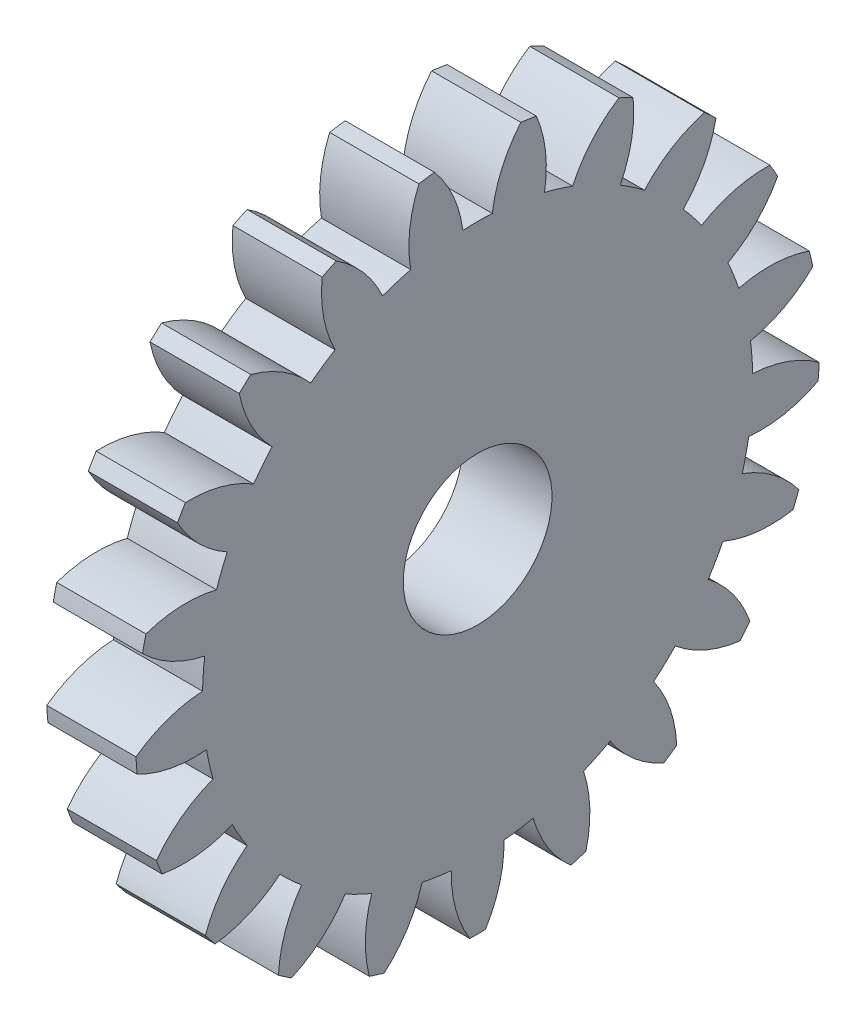
SolidWorks part; units mm, degrees
ref_plane "Plane1" through (0, 0, 0) normal (0, 0, 1) x (1, 0, 0)
ref_plane "Plane2" through (0, 0, 0) normal (0, 1, 0) x (1, 0, 0)
ref_plane "Plane3" through (0, 0, 0) normal (1, 0, 0) x (0, 0, -1)
sketch "HoldingSke" plane through (0, 0, 0) normal (0, 1, 0) x (1, 0, 0)
  line L0 (0, 0) -> (0.9336, -0.3584)
  line L1 (-15, 0) -> (100, 0) construction
  line L2 (0, 0) -> (-2.1039, 2.3779)
  line L3 (0, 0) -> (-11.863, 4.5341)
  line L4 (0, 0) -> (8.0624, 3.0949)
  line L5 (0, 0) -> (-46.8476, -17.4728)
  line L6 (0, 0) -> (-9.9476, -6.7116)
  line L7 (-2.1039, 2.3779) -> (8.6586, 51.2059)
  line L8 (-76.2, 54.61) -> (-75.3, 54.61)
  line L9 (-71.009, 38.7566) -> (-53.1078, 45.2721)
  line L10 (-76.2, 71.12) -> (104.1128, 71.12)
  line L11 (0, 0) -> (-12, 0)
  line L12 (-76.2, 101.6) -> (-76.162, 101.6)
  line L13 (24.9733, 27.94) -> (52.9518, 28.4284)
  line L14 (24.9733, 27.94) -> (24.9743, 27.94)
  line L15 (24.9733, 27.94) -> (100.4006, 29.5858)
  line L16 (-63.627, -1) -> (-12.827, -1)
  circle A0 centre (0, 0) radius 2.5
  circle A1 centre (0, 0) radius 9.249
  circle A2 centre (0, 0) radius 37.5
  circle A3 centre (0, 0) radius 2.5
  dimension "MHD" = 18.498
  dimension "Hub_dia" = 75
  dimension "Bore" = 5
  dimension "MBD" = 5
  dimension "Num_teeth" = 21
  dimension "Pitch" = 1
  dimension "Overall_len" = 50
  dimension "Show_teeth" = 21
  dimension "Thickness" = 12
  dimension "OAL" = 50.0001
  dimension "T_dim" = 0.9
  dimension "Ap" = 20
  dimension "H" = 19.05
  dimension "Pitch_radius" = 180.3128
  dimension "Width" = 12
  dimension "Backlash" = 0.038
  dimension "Addendum_fac" = 1
  dimension "Dedendum_fac" = 1.25
  dimension "Clearance_fac" = 0.25
  dimension "Dedendum_add" = 0.001
  dimension "Module" = 1
sketch "BasProSke" plane through (0, 0, 0) normal (0, 1, 0) x (1, 0, 0)
  line L0 (-10, 0) -> (60, 0) construction
  line L1 (0, 0) -> (0, 11.5)
  line L2 (0, 0) -> (12, 0)
  line L3 (12, 0) -> (12, 11.5)
  line L4 (12, 11.5) -> (0, 11.5)
  dimension "Thickness" = 12
  dimension "Diameter" = 23
revolve "Base-Revolve" add sketch "BasProSke" angle 360 about L0
sketch "TooCutSke" plane through (0, 0, 0) normal (1, 0, 0) x (0, 0, -1)
  line L1 (0, 0) -> (0, 107) construction
  line L2 (0, 0) -> (-0.8511, 10.4654) construction
  line L3 (0, 0) -> (-3.1226, 20.7168) construction
  line L4 (-0.8511, 10.4654) -> (-1.5613, 10.3584) construction
  arc A0 (0.4953, 9.2357) -> (-0.4953, 9.2357) centre (0, 0) ccw
  arc A1 (1.4725, 11.431) -> (-1.4725, 11.431) centre (0, 0) ccw
  circle A2 centre (0, 0) radius 10.5 construction
  circle A3 centre (0, 0) radius 9.8668 construction
  arc A4 (-0.4953, 9.2357) -> (-1.4725, 11.431) centre (-4.6605, 8.6967) ccw
  arc A5 (1.4725, 11.431) -> (0.4953, 9.2357) centre (4.6605, 8.6967) ccw
  dimension "Root_dia" = 18.498
  dimension "Overcut_dia" = 23.0508
  dimension "Pitch_dia" = 21
  dimension "Base_dia" = 19.7335
  dimension "Flank_rad" = 4.2
  dimension "Half_ang" = 8.571
  dimension "Half_CT" = 0.7182
extrude "ToothCut" cut sketch "TooCutSke" along normal through all
fillet "Breaks" [suppressed] radius 0.02
fillet "RootFillets" [suppressed] radius 0.251
pattern_circular "TeethCuts" count 21 every 17.143 about axis through (-10, 0, 0) along (1, 0, 0) of "ToothCut", "RootFillets", "Breaks"
sketch "HubNeaOneSke" plane through (0, 0, 0) normal (-1, 0, 0) x (0, 0, 1)
  circle A0 centre (0, 0) radius 9.249
  dimension "Diameter" = 18.498
extrude "HubNearOne" [suppressed] add sketch "HubNeaOneSke" along normal blind 38.0001
sketch "HubNeaBotSke" plane through (0, 0, 0) normal (-1, 0, 0) x (0, 0, 1)
  circle A0 centre (0, 0) radius 9.249
  dimension "Diameter" = 18.498
extrude "HubNearBoth" [suppressed] add sketch "HubNeaBotSke" along normal blind 19
ref_plane "FarPln" through (12, 0, 0) normal (1, 0, 0) x (0, 0, -1)
sketch "HubFarSke" plane through (12, 0, 0) normal (1, 0, 0) x (0, 0, -1)
  circle A0 centre (0, 0) radius 9.249
  dimension "Diameter" = 18.498
extrude "HubFar" [suppressed] add sketch "HubFarSke" along normal blind 19
sketch "BorSke" plane through (0, 0, 0) normal (1, 0, 0) x (0, 0, -1)
  circle A0 centre (0, 0) radius 2.5
  dimension "Diameter" = 5
extrude "Bore" cut sketch "BorSke" along normal mid plane 100.0001
sketch "KeySke" plane through (0, 0, 0) normal (1, 0, 0) x (0, 0, -1)
  line L0 (-1, 0) -> (-1, 3.4)
  line L1 (-1, 3.4) -> (1, 3.4)
  line L2 (1, 3.4) -> (1, 0)
  line L3 (0, 0) -> (0, 34) construction
  line L4 (-1, 0) -> (1, 0)
  dimension "Offset" = 3.4
  dimension "Width" = 2
extrude "Keyway" [suppressed] cut sketch "KeySke" along normal mid plane 100.0001
pattern_circular "Keyway2" [suppressed] count 2 every 90 about axis through (-10, 0, 0) along (1, 0, 0)
sketch "Croquis1" plane through (0, 0, 0) normal (-1, 0, 0) x (0, 0, 1)
  line L1 (-12.6891, 12.6586) -> (14.0592, 12.6586)
  line L2 (-12.6891, 12.6586) -> (-12.6891, -12.7196)
  line L3 (-12.6891, -12.7196) -> (14.0592, -12.7196)
  line L4 (14.0592, 12.6586) -> (14.0592, -12.7196)
extrude "Cortar-Extruir1" cut sketch "Croquis1" against normal blind 9
equation "' \"Module@HoldingSke\" = 6.35"
equation "' \"Num_teeth@HoldingSke\" = 12"
equation "' \"Ap@HoldingSke\" =  20"
equation "' \"Ap@HoldingSke\" = 20"
equation "' \"Width@HoldingSke\" = 0.5 * 25.4"
equation "' \"Hub_dia@HoldingSke\"= 1 * 25.4"
equation "' \"Hub_dia@HoldingSke\" = 1 * 25.4"
equation "' \"Overall_len@HoldingSke\" = 1.0 * 25.4"
equation "' \"Bore@HoldingSke\" = 0.75 * 25.4"
equation "' \"T_dim@HoldingSke\" = 0.1 * 25.4"
equation "' \"Width@KeySke\" = 0.25 * 25.4"
equation "' \"Show_teeth@HoldingSke\" = 13"
equation "' \"Backlash@HoldingSke\" = 0.009 * 25.4"
equation "' \"Addendum_fac@HoldingSke\" = 1.0"
equation "' \"Dedendum_fac@HoldingSke\" = 1.25"
equation "' \"Dedendum_add@HoldingSke\" = 0.00005 * 25.4"
equation "' \"Clearance_fac@HoldingSke\" = 0.25"
equation "\"Pitch@HoldingSke\" = 1 / \"Module@HoldingSke\""
equation "\"Overcut_dia@TooCutSke\" = (\"Num_teeth@HoldingSke\" + 2 * \"Addendum_fac@HoldingSke\") / \"Pitch@HoldingSke\" + 0.002 * 25.4"
equation "\"Pitch_dia@TooCutSke\" = \"Num_teeth@HoldingSke\" / \"Pitch@HoldingSke\""
equation "\"Base_dia@TooCutSke\" = \"Num_teeth@HoldingSke\" / \"Pitch@HoldingSke\" * cos((\"Ap@HoldingSke\"  * 3.14159265 / 180))"
equation "\"Root_dia@TooCutSke\" = (\"Num_teeth@HoldingSke\" + 2) / \"Pitch@HoldingSke\" - 2 * (\"Addendum_fac@HoldingSke\" + \"Dedendum_fac@HoldingSke\") / \"Pitch@HoldingSke\" - \"Dedendum_add@HoldingSke\" * 2"
equation "\"Half_ang@TooCutSke\" = 180 / \"Num_teeth@HoldingSke\""
equation "\"Half_CT@TooCutSke\" = \"Num_teeth@HoldingSke\" / \"Pitch@HoldingSke\" * sin((3.14159265 / 2 / \"Num_teeth@HoldingSke\")) / 2 - 7 * \"Backlash@HoldingSke\" / 4"
equation "\"Flank_rad@TooCutSke\" = \"Num_teeth@HoldingSke\" / \"Pitch@HoldingSke\" / 5"
equation "\"Radius@RootFillets\" = \"Clearance_fac@HoldingSke\" / \"Pitch@HoldingSke\" + \"Dedendum_add@HoldingSke\""
equation "\"Break_rad@Breaks\" = 0.02 / \"Pitch@HoldingSke\""
equation "\"Thickness@HoldingSke\" = \"Width@HoldingSke\""
equation "\"OAL@HoldingSke\" = \"Thickness@HoldingSke\""
equation "\"MHD@HoldingSke\" = (\"Num_teeth@HoldingSke\" + 2) / \"Pitch@HoldingSke\" - 2 * (\"Addendum_fac@HoldingSke\" + \"Dedendum_fac@HoldingSke\")  / \"Pitch@HoldingSke\" - \"Dedendum_add@HoldingSke\" * 2"
equation "\"MBD@HoldingSke\" = (\"Num_teeth@HoldingSke\" + 2) / \"Pitch@HoldingSke\" - 2 * (\"Addendum_fac@HoldingSke\" + \"Dedendum_fac@HoldingSke\")  / \"Pitch@HoldingSke\" - \"Dedendum_add@HoldingSke\" * 2 - 0.002 * 25.4"
equation "\"MHD@HoldingSke\" = ((sgn( \"MHD@HoldingSke\" - \"Hub_dia@HoldingSke\" )-1)*( \"MHD@HoldingSke\" - \"Hub_dia@HoldingSke\" ))/-2+ \"Hub_dia@HoldingSke\""
equation "\"MBD@HoldingSke\" = ((sgn( \"MBD@HoldingSke\" - \"Bore@HoldingSke\" )-1)*( \"MBD@HoldingSke\" - \"Bore@HoldingSke\" ))/-2+ \"Bore@HoldingSke\""
equation "\"OAL@HoldingSke\" = ((sgn( \"OAL@HoldingSke\" - \"Overall_len@HoldingSke\" )+1)*( \"OAL@HoldingSke\" - \"Overall_len@HoldingSke\" ))/2 + \"Overall_len@HoldingSke\" + 0.000002 * 25.4"
equation "\"Num_teeth@TeethCuts\" = int( \"Show_teeth@HoldingSke\" ) + 1"
equation "\"Num_teeth@TeethCuts\" = ((sgn( \"Num_teeth@TeethCuts\" - \"Num_teeth@HoldingSke\" )-1)*( \"Num_teeth@TeethCuts\" - \"Num_teeth@HoldingSke\" ))/-2+ \"Num_teeth@HoldingSke\""
equation "\"Num_teeth@TeethCuts\" = ((sgn( \"Num_teeth@TeethCuts\" - 2.0)+1)*( \"Num_teeth@TeethCuts\" - 2.0))/2 +2.0"
equation "\"Angle@TeethCuts\" = 360.0 / \"Num_teeth@HoldingSke\""
equation "\"Diameter@BasProSke\" = (\"Num_teeth@HoldingSke\" + 2 * \"Addendum_fac@HoldingSke\") / \"Pitch@HoldingSke\""
equation "\"Thickness@BasProSke\"  = \"Thickness@HoldingSke\""
equation "' \"Fillet_rad@BasProSke\" =  \"Thickness@HoldingSke\" * 0.05"
equation "' \"Fillet_rad@BasProSke\" = \"Thickness@HoldingSke\" * 0.05"
equation "\"MHD@HoldingSke\" = ((sgn( \"MHD@HoldingSke\" - \"Root_dia@TooCutSke\" )-1)*( \"MHD@HoldingSke\" - \"Root_dia@TooCutSke\" ))/-2+ \"Root_dia@TooCutSke\""
equation "\"Diameter@HubNeaOneSke\" = \"MHD@HoldingSke\""
equation "\"Length@HubNearOne\" = \"OAL@HoldingSke\" - \"Thickness@BasProSke\""
equation "\"Diameter@HubNeaBotSke\" = \"MHD@HoldingSke\""
equation "\"Length@HubNearBoth\" = ( \"OAL@HoldingSke\" - \"Thickness@BasProSke\" ) / 2.0"
equation "\"Thickness@FarPln\" = \"Thickness@BasProSke\""
equation "\"Diameter@HubFarSke\" = \"MHD@HoldingSke\""
equation "\"Length@HubFar\" = ( \"OAL@HoldingSke\" - \"Thickness@BasProSke\" ) / 2.0"
equation "\"Diameter@BorSke\" = \"MBD@HoldingSke\""
equation "\"D1@Bore\" = \"OAL@HoldingSke\" * 2.0"
equation "\"D1@Keyway\" = \"OAL@HoldingSke\" * 2.0"
equation "\"Offset@KeySke\" = \"T_dim@HoldingSke\" + \"MBD@HoldingSke\" / 2.0"
